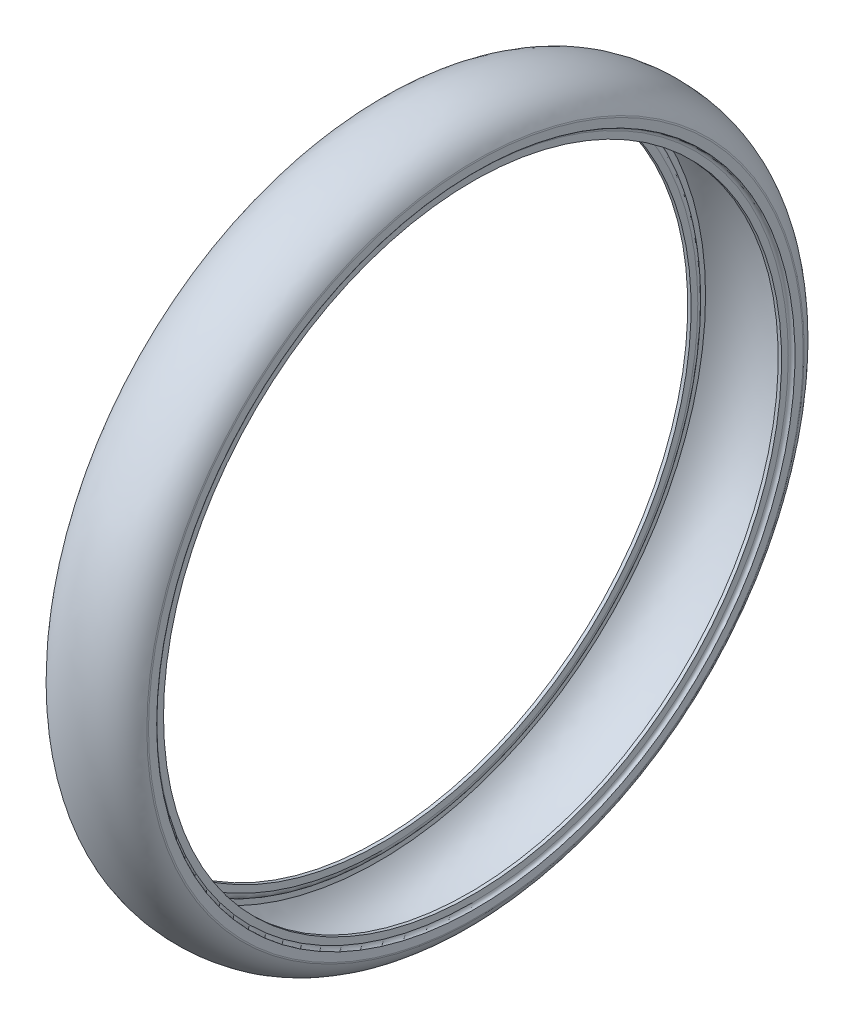
SolidWorks part; units mm, degrees
ref_plane "Front Plane" through (0, 0, 0) normal (0, 0, 1) x (1, 0, 0)
ref_plane "Top Plane" through (0, 0, 0) normal (0, 1, 0) x (1, 0, 0)
ref_plane "Right Plane" through (0, 0, 0) normal (1, 0, 0) x (0, 0, -1)
sketch "Sketch3" plane through (0, 0, 0) normal (0, 0, 1) x (1, 0, 0)
  line L0 (-69.7003, 0) -> (88.5744, 0) construction
  line L1 (0, 0) -> (0, 248.847) construction
  line L2 (29.9222, 190.4533) -> (29.9592, 195.3775)
  line L3 (-27.9973, 184.4533) -> (-27.9973, 188.4533)
  line L4 (-29.9973, 190.4533) -> (-29.9222, 190.4533)
  line L5 (-29.9222, 190.4533) -> (-29.9222, 195.0112)
  line L6 (29.9973, 190.4533) -> (29.9222, 190.4533)
  line L7 (27.9973, 184.4533) -> (27.9973, 188.4533)
  line L8 (-25.9973, 184.4533) -> (-25.9973, 188.4533)
  line L9 (-27.9222, 191.8729) -> (-27.9222, 191.8729)
  line L10 (-27.9222, 191.8729) -> (-27.9222, 195.0112)
  line L11 (27.9328, 191.8794) -> (27.9593, 195.3926)
  line L12 (27.9328, 191.8794) -> (27.9328, 191.8794)
  line L13 (25.9973, 184.4533) -> (25.9973, 188.4533)
  line L14 (-27.9973, 184.4533) -> (-25.9973, 184.4533)
  line L15 (25.9973, 184.4533) -> (27.9973, 184.4533)
  arc A0 (-27.9973, 188.4533) -> (-29.9973, 190.4533) centre (-29.9973, 188.4533) ccw
  arc A1 (29.9973, 190.4533) -> (27.9973, 188.4533) centre (29.9973, 188.4533) ccw
  arc A2 (29.9592, 195.3775) -> (29.7952, 196.1861) centre (27.9593, 195.3926) ccw
  arc A3 (-29.9222, 195.0112) -> (-29.557, 196.1632) centre (-27.9222, 195.0112) cw
  arc A4 (-25.9973, 188.4533) -> (-27.9222, 191.8729) centre (-29.9973, 188.4533) ccw
  arc A5 (-27.9222, 195.0112) -> (-27.9222, 195.0112) centre (-27.9222, 195.0112) cw
  arc A6 (27.9593, 195.3926) -> (27.9593, 195.3926) centre (27.9593, 195.3926) ccw
  arc A7 (27.9328, 191.8794) -> (25.9973, 188.4533) centre (29.9973, 188.4533) ccw
  spline S0 degree 3 poles (-29.557, 196.1632) (-21.5303, 207.5533) (-1.3198, 214.3567) (24.6515, 208.087) (29.7952, 196.1861) knots 0.008654 0.008654 0.008654 0.008654 0.499414 0.989683 0.989683 0.989683 0.989683
  spline S1 degree 1 poles (-27.9222, 195.0112) (27.9593, 195.3926) knots 0 0 1 1 construction
  spline S2 degree 3 poles (-27.9222, 195.0112) (-27.6854, 195.3471) (-27.1979, 196.0185) (-26.2212, 197.2835) (-24.9727, 198.7573) (-23.4392, 200.3513) (-21.3451, 202.2596) (-18.6363, 204.2587) (-15.2326, 206.1091) (-11.6626, 207.4723) (-6.6718, 208.7101) (0.0429, 209.2865) (8.671, 208.79) (15.4436, 207.0045) (20.1946, 204.566) (23.3323, 202.1922) (25.5394, 199.701) (27.0188, 197.3762) (27.6724, 196.0563) (27.9593, 195.3926) knots 0.008654 0.008654 0.008654 0.008654 0.023982 0.039311 0.069968 0.100625 0.131282 0.192597 0.253911 0.315225 0.37654 0.499168 0.621797 0.744426 0.80574 0.867054 0.928369 0.959026 0.989683 0.989683 0.989683 0.989683
  spline S3 degree 1 poles (-29.1483, 195.8752) (29.3362, 195.9877) knots 0 0 1 1 construction
  spline S4 degree 3 poles (-29.1483, 195.8752) (-28.6641, 196.5623) (-27.6394, 197.9319) (-26.0897, 199.7595) (-24.4868, 201.4266) (-22.2946, 203.4242) (-19.4459, 205.5273) (-15.8603, 207.4764) (-12.1091, 208.9084) (-6.8923, 210.2005) (0.0291, 210.7911) (8.8831, 210.2835) (15.9515, 208.4298) (20.9898, 205.8469) (24.3548, 203.3034) (26.7359, 200.6166) (28.329, 198.1122) (29.0286, 196.6993) (29.3362, 195.9877) knots 0.008654 0.008654 0.008654 0.008654 0.039311 0.069968 0.100625 0.131282 0.192597 0.253911 0.315225 0.37654 0.499168 0.621797 0.744426 0.80574 0.867054 0.928369 0.959026 0.989683 0.989683 0.989683 0.989683 construction
  point P5 (0, 184.84)
  point P6 (-27.9973, 184.4533)
  point P19 (-27.9973, 190.4533)
  point P22 (27.9973, 190.4533)
  dimension "D6" = 70
  dimension "D7" = 2
  dimension "D8" = 2
  dimension "D9" = 2
  dimension "D1" = 184.84
  dimension "D2" = 28
  dimension "D3" = 6
  dimension "D4" = 2
  dimension "D5" = 1.9248
  dimension "D10" = 0.5
revolve "Revolve1" add sketch "Sketch3" angle 360 about L0
